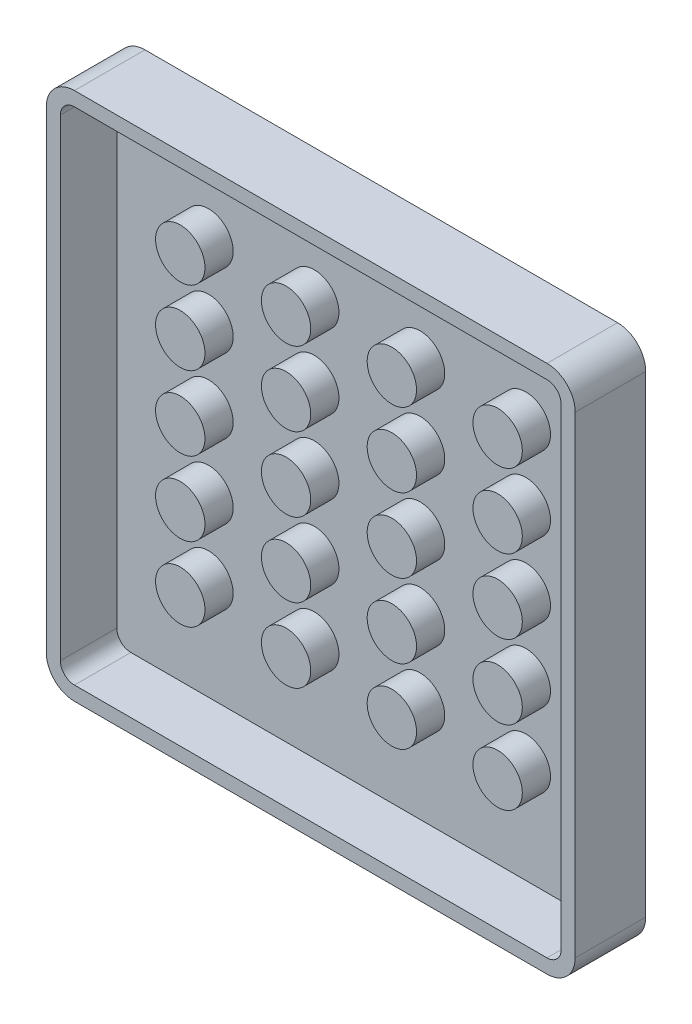
SolidWorks part; units mm, degrees
ref_plane "Front Plane" through (0, 0, 0) normal (0, 0, 1) x (1, 0, 0)
ref_plane "Top Plane" through (0, 0, 0) normal (0, 1, 0) x (1, 0, 0)
ref_plane "Right Plane" through (0, 0, 0) normal (1, 0, 0) x (0, 0, -1)
sketch "Sketch1" plane through (0, 0, 0) normal (0, 0, 1) x (1, 0, 0)
  line L1 (0, 0) -> (75, 0)
  line L2 (0, 0) -> (0, 75)
  line L3 (0, 75) -> (75, 75)
  line L4 (75, 0) -> (75, 75)
  dimension "D1" = 75
  dimension "D2" = 75
extrude "Boss-Extrude1" add sketch "Sketch1" along normal blind 10
fillet "Fillet1" radius 4 4 edges at (0, 0, 5) (75, 0, 5) (75, 75, 5) (0, 75, 5)
shell "Shell1" thickness 2
sketch "Sketch2" plane through (0, 0, 2) normal (0, 0, 1) x (1, 0, 0)
  circle A20 centre (15, 58.5) radius 3.5
  circle A21 centre (30, 58.5) radius 3.5
  circle A22 centre (45, 58.5) radius 3.5
  circle A23 centre (60, 58.5) radius 3.5
  circle A24 centre (30, 48) radius 3.5
  circle A25 centre (45, 48) radius 3.5
  circle A26 centre (60, 48) radius 3.5
  circle A27 centre (30, 37.5) radius 3.5
  circle A28 centre (45, 37.5) radius 3.5
  circle A29 centre (60, 37.5) radius 3.5
  circle A30 centre (30, 27) radius 3.5
  circle A31 centre (45, 27) radius 3.5
  circle A32 centre (60, 27) radius 3.5
  circle A33 centre (30, 16.5) radius 3.5
  circle A34 centre (45, 16.5) radius 3.5
  circle A35 centre (60, 16.5) radius 3.5
  circle A36 centre (15, 48) radius 3.5
  circle A37 centre (15, 37.5) radius 3.5
  circle A38 centre (15, 27) radius 3.5
  circle A39 centre (15, 16.5) radius 3.5
  dimension "D1" = 7
  dimension "D2" = 4
  dimension "D3" = 5
extrude "Boss-Extrude2" add sketch "Sketch2" along normal blind 4
